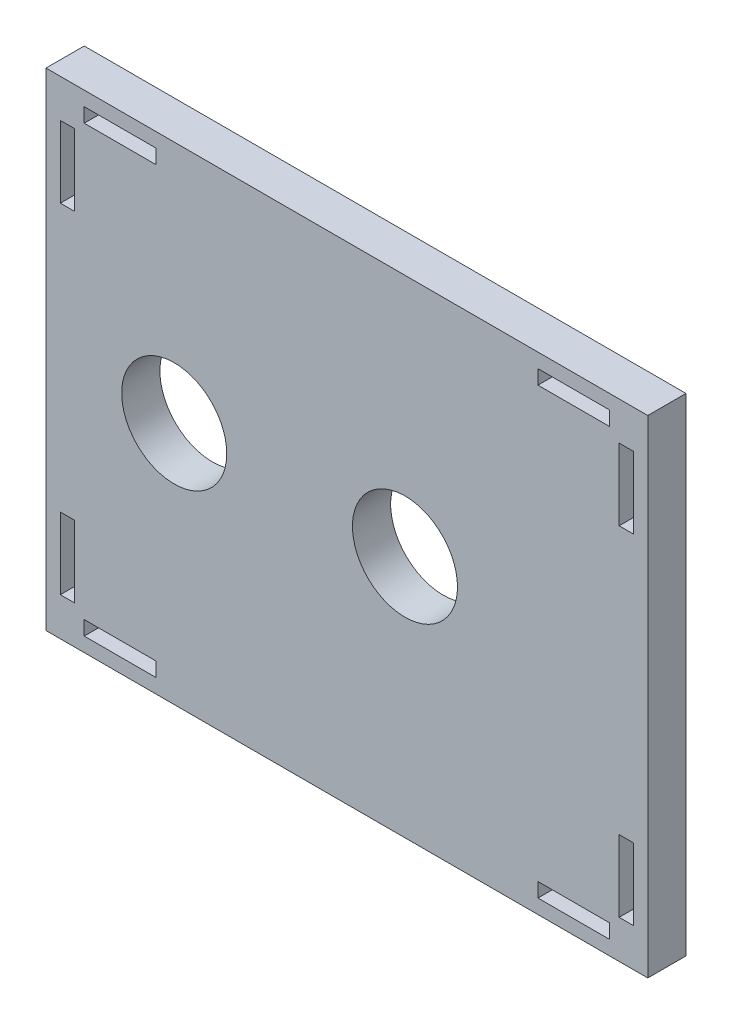
SolidWorks part; units mm, degrees
ref_plane "Front Plane" through (0, 0, 0) normal (0, 0, 1) x (1, 0, 0)
ref_plane "Top Plane" through (0, 0, 0) normal (0, 1, 0) x (1, 0, 0)
ref_plane "Right Plane" through (0, 0, 0) normal (1, 0, 0) x (0, 0, -1)
sketch "Sketch1" plane through (0, 0, 0) normal (0, 0, 1) x (1, 0, 0)
  line L0 (-48, -28) -> (-45, -28)
  line L1 (-51, 51) -> (75, 51)
  line L2 (-51, 51) -> (-51, -51)
  line L3 (-51, -51) -> (75, -51)
  line L4 (75, 51) -> (75, -51)
  line L5 (-48, 43) -> (-45, 43)
  line L6 (-48, 43) -> (-48, 28)
  line L7 (-48, 28) -> (-45, 28)
  line L8 (-45, 43) -> (-45, 28)
  line L9 (-48, 43) -> (-45, 28) construction
  line L10 (-48, 28) -> (-45, 43) construction
  line L11 (-48, -28) -> (-48, -43)
  line L12 (-48, -43) -> (-45, -43)
  line L13 (-45, -28) -> (-45, -43)
  line L14 (-48, -28) -> (-45, -43) construction
  line L15 (-48, -43) -> (-45, -28) construction
  line L16 (69, 43) -> (72, 43)
  line L17 (69, 43) -> (69, 28)
  line L18 (69, 28) -> (72, 28)
  line L19 (72, 43) -> (72, 28)
  line L20 (69, 43) -> (72, 28) construction
  line L21 (69, 28) -> (72, 43) construction
  line L22 (69, -28) -> (72, -28)
  line L23 (69, -28) -> (69, -43)
  line L24 (69, -43) -> (72, -43)
  line L25 (72, -28) -> (72, -43)
  line L26 (69, -28) -> (72, -43) construction
  line L27 (69, -43) -> (72, -28) construction
  line L29 (-43, 48) -> (-28, 48)
  line L30 (-43, 48) -> (-43, 45)
  line L31 (-43, 45) -> (-28, 45)
  line L32 (-28, 48) -> (-28, 45)
  line L33 (-43, 48) -> (-28, 45) construction
  line L34 (-43, 45) -> (-28, 48) construction
  line L35 (52, 48) -> (67, 48)
  line L36 (52, 48) -> (52, 45)
  line L37 (52, 45) -> (67, 45)
  line L38 (67, 48) -> (67, 45)
  line L39 (52, 48) -> (67, 45) construction
  line L40 (52, 45) -> (67, 48) construction
  line L41 (-43, -45) -> (-28, -45)
  line L42 (52, -45) -> (67, -45)
  line L43 (52, -45) -> (52, -48)
  line L44 (52, -48) -> (67, -48)
  line L45 (67, -45) -> (67, -48)
  line L46 (52, -45) -> (67, -48) construction
  line L47 (52, -48) -> (67, -45) construction
  line L48 (-43, -45) -> (-43, -48)
  line L49 (-43, -48) -> (-28, -48)
  line L50 (-28, -45) -> (-28, -48)
  line L51 (-43, -45) -> (-28, -48) construction
  line L52 (-43, -48) -> (-28, -45) construction
  circle A0 centre (-24.1573, 0) radius 11
  circle A1 centre (24.1573, 0) radius 11
  point P4 (-35.5, 46.5)
  point P6 (0, 0)
  point P14 (-46.5, -35.5)
  point P16 (-46.5, 35.5)
  point P25 (59.5, 46.5)
  point P30 (-35.5, -46.5)
  point P31 (59.5, -46.5)
  point P33 (70.5, 35.5)
  point P43 (70.5, -35.5)
extrude "Boss-Extrude1" add sketch "Sketch1" along normal blind 8
